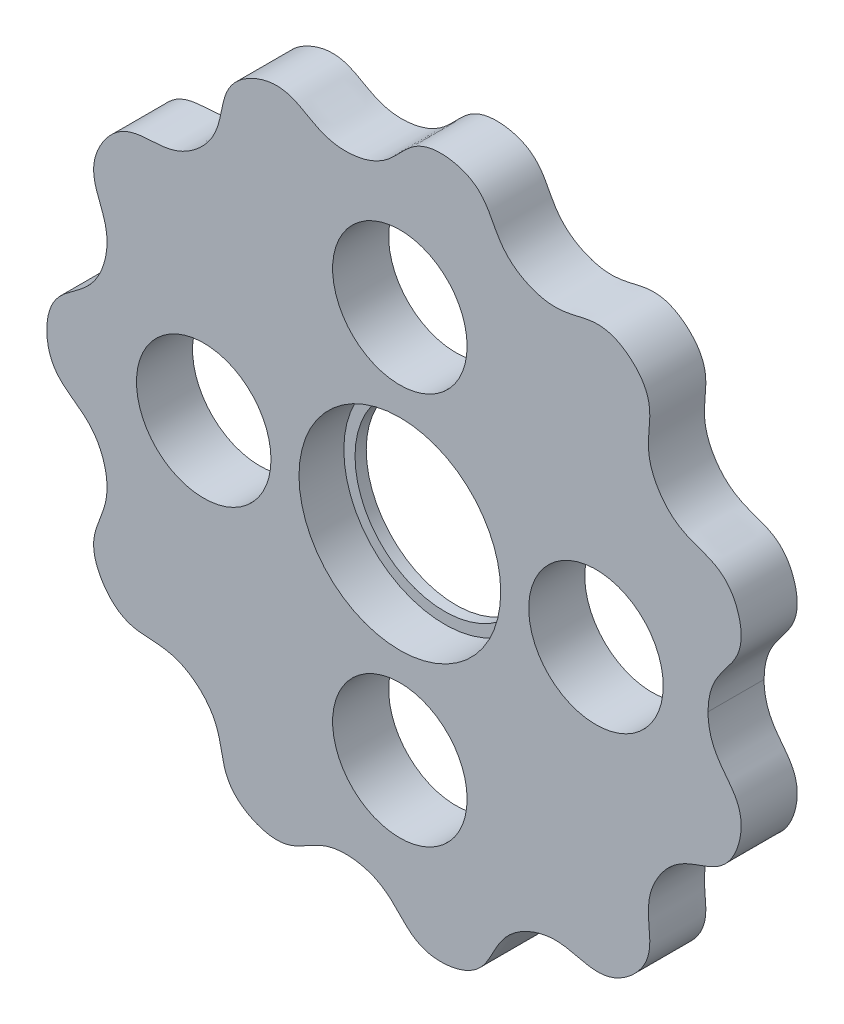
SolidWorks part; units mm, degrees
material "ABS"
ref_plane "Front Plane" through (0, 0, 0) normal (0, 0, 1) x (1, 0, 0)
ref_plane "Top Plane" through (0, 0, 0) normal (0, 1, 0) x (1, 0, 0)
ref_plane "Right Plane" through (0, 0, 0) normal (1, 0, 0) x (0, 0, -1)
sketch "Sketch2" plane through (0, 0, 0) normal (0, 0, 1) x (1, 0, 0)
  line L0 (2, 0) -> (19.5, 0) construction
  line L1 (2, 0) -> (2, 17.5) construction
  line L2 (2, 0) -> (-15.5, 0) construction
  line L3 (2, 0) -> (2, -17.5) construction
  circle A0 centre (2, 0) radius 9
  circle A1 centre (19.5, 0) radius 6
  circle A2 centre (2, 17.5) radius 6
  circle A3 centre (-15.5, 0) radius 6
  circle A4 centre (2, -17.5) radius 6
  spline S0 degree 5 poles (-29.5, 0) (-29.5, -0.4067) (-29.455, -0.949) (-29.3238, -1.6054) (-29.0375, -2.3182) (-28.3803, -3.2214) (-27.7103, -3.8007) (-26.5167, -4.5987) (-25.0866, -5.7216) (-24.3432, -7.4522) (-23.9115, -9.3055) (-24.2824, -11.0623) (-24.7976, -12.2658) (-25.1298, -13.1071) (-25.366, -14.207) (-25.3495, -15.0803) (-25.0309, -16.2152) (-24.4048, -17.3052) (-23.5876, -18.2113) (-22.8571, -18.7303) (-21.8159, -19.1349) (-20.939, -19.2599) (-19.5035, -19.2859) (-17.6934, -19.4575) (-16.1323, -20.5114) (-14.7672, -21.8371) (-14.1294, -23.5155) (-13.9122, -24.8065) (-13.7368, -25.6939) (-13.3409, -26.7469) (-12.8548, -27.4726) (-11.9732, -28.2551) (-10.8572, -28.8336) (-9.6799, -29.1541) (-8.7847, -29.1957) (-7.6901, -28.9731) (-6.8849, -28.6043) (-5.6631, -27.85) (-4.0476, -27.0157) (-2.1646, -27.0583) (-0.2994, -27.4356) (1.1445, -28.5028) (2.0252, -29.4713) (2.6525, -30.123) (3.5549, -30.7948) (4.3561, -31.1425) (5.5208, -31.3242) (6.7724, -31.2075) (7.9361, -30.8406) (8.7117, -30.3917) (9.5122, -29.6126) (9.9902, -28.867) (10.6102, -27.5719) (11.5182, -25.9967) (13.1254, -25.0145) (14.8984, -24.3235) (16.6901, -24.4405) (17.9546, -24.7792) (18.8347, -24.9883) (19.957, -25.0656) (20.819, -24.9249) (21.8971, -24.4481) (22.8869, -23.6733) (23.6675, -22.7354) (24.0772, -21.9385) (24.3295, -20.8503) (24.3284, -19.9646) (24.1499, -18.54) (24.0621, -16.7238) (24.8831, -15.0287) (26.0011, -13.4888) (27.5716, -12.6186) (28.8185, -12.2199) (29.6719, -11.92) (30.6579, -11.3782) (31.307, -10.7939) (31.9561, -9.8099) (32.3699, -8.6229) (32.5195, -7.412) (32.4334, -6.52) (32.0572, -5.4682) (31.5776, -4.7236) (30.6571, -3.6217) (29.903, -2.5643) (29.5937, -1.4392) (29.5, -0.6542) (29.5, 0) knots 0.5 0.5 0.5 0.5 0.5 0.5 0.509091 0.512121 0.515152 0.518182 0.527273 0.530303 0.545455 0.557576 0.560606 0.569697 0.572727 0.575758 0.578788 0.587879 0.590909 0.6 0.60303 0.606061 0.609091 0.618182 0.621212 0.636364 0.648485 0.651515 0.660606 0.663636 0.666667 0.669697 0.678788 0.681818 0.690909 0.693939 0.69697 0.7 0.709091 0.712121 0.727273 0.739394 0.742424 0.751515 0.754545 0.757576 0.760606 0.769697 0.772727 0.781818 0.784848 0.787879 0.790909 0.8 0.80303 0.818182 0.830303 0.833333 0.842424 0.845455 0.848485 0.851515 0.860606 0.863636 0.872727 0.875758 0.878788 0.881818 0.890909 0.893939 0.909091 0.921212 0.924242 0.933333 0.936364 0.939394 0.942424 0.951515 0.954545 0.963636 0.966667 0.969697 0.972727 0.981818 0.984848 1 1 1 1 1 1 weights 1 1 1 1 1 1 1 1 1 1 1 1 1 1 1 1 1 1 1 1 1 1 1 1 1 1 1 1 1 1 1 1 1 1 1 1 1 1 1 1 1 1 1 1 1 1 1 1 1 1 1 1 1 1 1 1 1 1 1 1 1 1 1 1 1 1 1 1 1 1 1 1 1 1 1 1 1 1 1 1 1 1 1 1 1 1 1
  spline S1 degree 5 poles (29.5, 0) (29.5, 0.6542) (29.5937, 1.4392) (29.8687, 2.4393) (30.5063, 3.4102) (31.3265, 4.4231) (31.7831, 5.0427) (32.2601, 5.9216) (32.4902, 6.7642) (32.5043, 7.9429) (32.2107, 9.1651) (31.6819, 10.2648) (31.1271, 10.9686) (30.2421, 11.6501) (29.436, 12.0171) (28.0659, 12.4465) (26.3775, 13.1211) (25.1766, 14.5721) (24.2402, 16.2287) (24.1012, 18.0188) (24.2564, 19.3187) (24.3381, 20.2195) (24.2549, 21.3414) (23.993, 22.1747) (23.3676, 23.1739) (22.4598, 24.0433) (21.4204, 24.6825) (20.5733, 24.9747) (19.4603, 25.0695) (18.5837, 24.9424) (17.199, 24.5629) (15.4138, 24.2176) (13.6191, 24.789) (11.9358, 25.6764) (10.851, 27.1072) (10.2788, 28.2846) (9.8605, 29.0866) (9.184, 29.9855) (8.5132, 30.5448) (7.4468, 31.0473) (6.2131, 31.288) (4.9931, 31.2637) (4.1225, 31.0515) (3.1349, 30.5295) (2.4662, 29.9487) (1.5065, 28.8809) (0.1914, 27.6252) (-1.6273, 27.1356) (-3.5232, 26.9721) (-5.2093, 27.5892) (-6.3272, 28.2704) (-7.1127, 28.719) (-8.1678, 29.1093) (-9.0346, 29.2172) (-10.2033, 29.0634) (-11.3713, 28.5989) (-12.3845, 27.9189) (-13.0022, 27.2697) (-13.5507, 26.2966) (-13.7993, 25.4465) (-14.0294, 24.0293) (-14.4568, 22.262) (-15.7221, 20.8668) (-17.2286, 19.7043) (-18.9807, 19.3119) (-20.2894, 19.2805) (-21.1928, 19.2332) (-22.2914, 18.9912) (-23.0789, 18.6134) (-23.9789, 17.8521) (-24.7104, 16.8298) (-25.1951, 15.7101) (-25.3637, 14.8299) (-25.2992, 13.7148) (-25.0487, 12.8652) (-24.476, 11.5486) (-23.8801, 9.8308) (-24.1902, 7.973) (-24.8291, 6.1805) (-26.0909, 4.9031) (-27.1749, 4.1692) (-27.9093, 3.6411) (-28.7026, 2.8435) (-29.1609, 2.0999) (-29.3913, 1.3486) (-29.485, 0.6778) (-29.5, 0.1356) (-29.5, 0) knots 0 0 0 0 0 0 0.015152 0.018182 0.024242 0.027273 0.030303 0.033333 0.042424 0.045455 0.054545 0.057576 0.060606 0.063636 0.072727 0.075758 0.090909 0.10303 0.106061 0.115152 0.118182 0.121212 0.124242 0.133333 0.136364 0.145455 0.148485 0.151515 0.154545 0.163636 0.166667 0.181818 0.193939 0.19697 0.206061 0.209091 0.212121 0.215152 0.224242 0.227273 0.236364 0.239394 0.242424 0.245455 0.254545 0.257576 0.272727 0.284848 0.287879 0.29697 0.3 0.30303 0.306061 0.315152 0.318182 0.327273 0.330303 0.333333 0.336364 0.345455 0.348485 0.363636 0.375758 0.378788 0.387879 0.390909 0.393939 0.39697 0.406061 0.409091 0.418182 0.421212 0.424242 0.427273 0.436364 0.439394 0.454545 0.466667 0.469697 0.478788 0.481818 0.484848 0.487879 0.49697 0.5 0.5 0.5 0.5 0.5 0.5 weights 1 1 1 1 1 1 1 1 1 1 1 1 1 1 1 1 1 1 1 1 1 1 1 1 1 1 1 1 1 1 1 1 1 1 1 1 1 1 1 1 1 1 1 1 1 1 1 1 1 1 1 1 1 1 1 1 1 1 1 1 1 1 1 1 1 1 1 1 1 1 1 1 1 1 1 1 1 1 1 1 1 1 1 1 1 1 1 1
  point P3 (0, 0)
  point P4 (2, 0)
extrude "Boss-Extrude2" add sketch "Sketch2" along normal blind 5
sketch "Sketch3" plane through (0, 0, 0) normal (0, 0, -1) x (-1, 0, 0)
  line L0 (0, 0) -> (-2, 0) construction
  circle A0 centre (-2, 0) radius 8
  circle A1 centre (-2, 0) radius 9
  dimension "D2" = 18
  dimension "D3" = 16
  dimension "D1" = 2
extrude "Boss-Extrude3" add sketch "Sketch3" against normal blind 1
